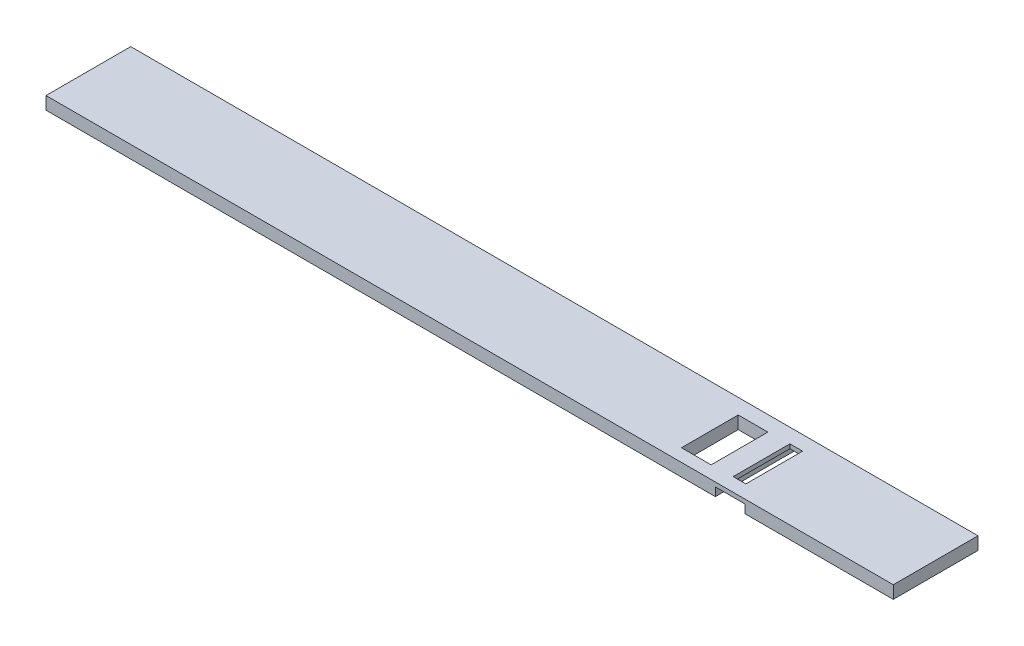
SolidWorks part; units mm, degrees
ref_plane "Plan de face" through (0, 0, 0) normal (0, 0, 1) x (1, 0, 0)
ref_plane "Plan de dessus" through (0, 0, 0) normal (0, 1, 0) x (1, 0, 0)
ref_plane "Plan de droite" through (0, 0, 0) normal (1, 0, 0) x (0, 0, -1)
sketch "Sketch1" plane through (0, 0, 0) normal (0, 1, 0) x (1, 0, 0)
  line L1 (0, 0) -> (1000, 0)
  line L2 (0, 0) -> (0, 100)
  line L3 (0, 100) -> (1000, 100)
  line L4 (1000, 0) -> (1000, 100)
  dimension "D1" = 1000
  dimension "D2" = 100
extrude "Boss-Extrude1" add sketch "Sketch1" along normal blind 15
sketch "Sketch2" plane through (0, 15, 0) normal (0, 1, 0) x (1, 0, 0)
  line L0 (0, 100) -> (0, 0) construction
  line L1 (735, 15) -> (770, 15)
  line L2 (735, 15) -> (735, 82)
  line L3 (735, 82) -> (770, 82)
  line L4 (770, 15) -> (770, 82)
  line L5 (0, 0) -> (1000, 0) construction
  dimension "D1" = 67
  dimension "D2" = 35
  dimension "D3" = 735
  dimension "D4" = 15
extrude "Cut-Extrude1" cut sketch "Sketch2" against normal blind 15
sketch "Sketch4" plane through (0, 0, 0) normal (0, 0, 1) x (1, 0, 0)
  line L0 (0, 0) -> (1000, 0) construction
  line L1 (790, 0) -> (825, 0)
  line L2 (790, 0) -> (790, 10)
  line L3 (790, 10) -> (825, 10)
  line L4 (825, 0) -> (825, 10)
  line L5 (0, 15) -> (0, 0) construction
  dimension "D1" = 35
  dimension "D2" = 10
  dimension "D3" = 790
extrude "Cut-Extrude2" cut sketch "Sketch4" against normal blind 100
sketch "Sketch5" plane through (0, 15, 0) normal (0, 1, 0) x (1, 0, 0)
  line L0 (0, 0) -> (1000, 0) construction
  line L1 (795, 83) -> (810, 83)
  line L2 (795, 83) -> (795, 16)
  line L3 (795, 16) -> (810, 16)
  line L4 (810, 83) -> (810, 16)
  line L5 (0, 100) -> (0, 0) construction
  dimension "D1" = 15
  dimension "D2" = 67
  dimension "D3" = 16
  dimension "D4" = 795
extrude "Cut-Extrude4" cut sketch "Sketch5" against normal blind 100
